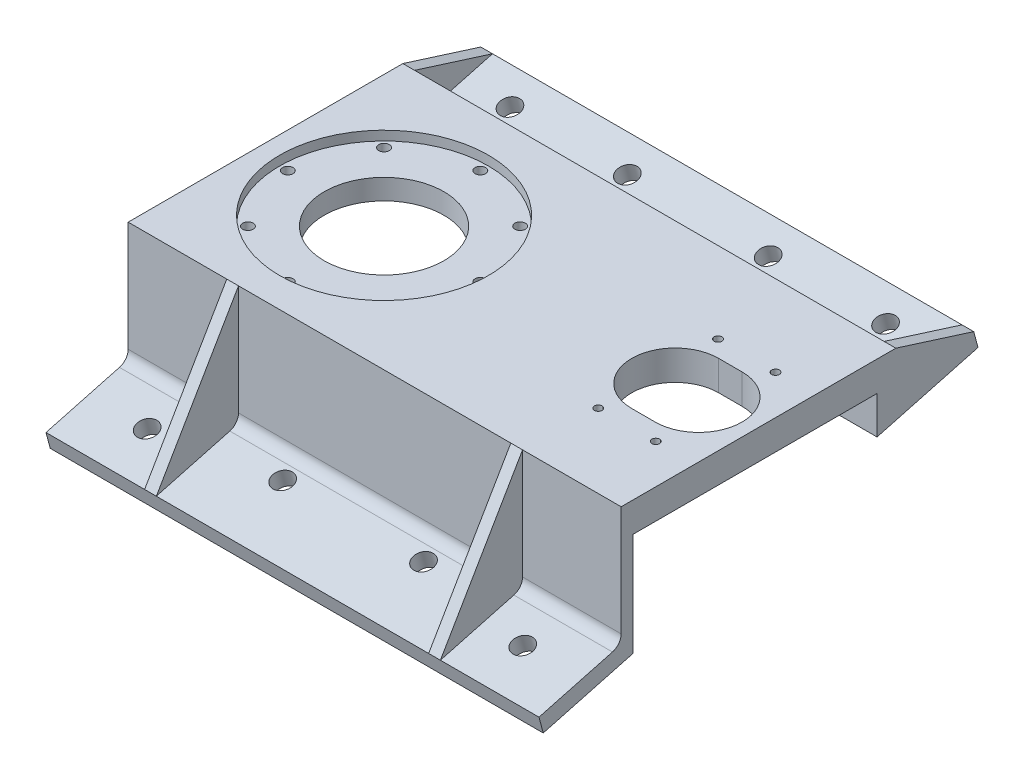
SolidWorks part; units mm, degrees
material "1060 合金"
ref_plane "前视基准面" through (0, 0, 0) normal (0, 0, 1) x (1, 0, 0)
ref_plane "上视基准面" through (0, 0, 0) normal (0, 1, 0) x (1, 0, 0)
ref_plane "右视基准面" through (0, 0, 0) normal (1, 0, 0) x (0, 0, -1)
sketch "草图1" plane through (0, 0, 0) normal (0, 1, 0) x (1, 0, 0)
  line L0 (0, 0) -> (170, 0) construction
  line L1 (170, 31.93) -> (170, -31.93)
  line L2 (15.8391, 73.3084) -> (162.1119, 41.7045)
  line L3 (15.8391, -73.3084) -> (162.1119, -41.7045)
  arc A0 (15.8391, 73.3084) -> (15.8391, -73.3084) centre (0, 0) ccw
  arc A1 (162.1119, -41.7045) -> (170, -31.93) centre (160, -31.93) ccw
  arc A2 (170, 31.93) -> (162.1119, 41.7045) centre (160, 31.93) ccw
  point P6 (170, 0)
  dimension "D1" = 150
  dimension "D4" = 20
  dimension "D5" = 20
  dimension "D2" = 170
  dimension "D3" = 63.86
extrude "凸台-拉伸1" add sketch "草图1" along normal blind 30
sketch "草图2" plane through (0, 30, 0) normal (0, 1, 0) x (1, 0, 0)
  circle A0 centre (0, 0) radius 44.45
  dimension "D1" = 88.9
extrude "切除-拉伸1" cut sketch "草图2" against normal blind 4
sketch "草图3" plane through (0, 26, 0) normal (0, 1, 0) x (1, 0, 0)
  line L0 (0, 0) -> (0, 90.3276) construction
  circle A0 centre (0, 0) radius 25.5
  circle A1 centre (0, 41) radius 2.25
  circle A2 centre (28.9914, 28.9914) radius 2.25
  circle A3 centre (41, 0) radius 2.25
  circle A4 centre (28.9914, -28.9914) radius 2.25
  circle A5 centre (0, -41) radius 2.25
  circle A6 centre (-28.9914, -28.9914) radius 2.25
  circle A7 centre (-41, 0) radius 2.25
  circle A8 centre (-28.9914, 28.9914) radius 2.25
  dimension "D1" = 51
  dimension "D3" = 4.5
  dimension "D2" = 41
  dimension "D4" = 8
extrude "切除-拉伸2" cut sketch "草图3" against normal through all contours A2 | A3 | A4 | A5 | A6 | A7 | A8 | A1 | A0
sketch "草图4" plane through (0, 30, 0) normal (0, 1, 0) x (1, 0, 0)
  line L0 (0, 0) -> (134, 0) construction
  line L1 (124, 18.5) -> (134, 18.5)
  line L2 (124, -18.5) -> (134, -18.5)
  arc A0 (134, -18.5) -> (134, 18.5) centre (134, 0) ccw
  arc A1 (124, 18.5) -> (124, -18.5) centre (124, 0) ccw
  dimension "D2" = 37
  dimension "D3" = 37
  dimension "D1" = 134
  dimension "D4" = 10
extrude "切除-拉伸3" cut sketch "草图4" against normal through all
sketch "草图5" plane through (0, 30, 0) normal (0, 1, 0) x (1, 0, 0)
  arc A0 (134, -18.5) -> (134, 18.5) centre (134, 0) ccw construction
  arc A1 (124, 18.5) -> (124, -18.5) centre (124, 0) ccw construction
  arc A2 (134, -18.5) -> (134, 18.5) centre (134, 0) ccw construction
  arc A3 (124, 18.5) -> (124, -18.5) centre (124, 0) ccw construction
  circle A4 centre (116.75, 25.5) radius 1.65
  circle A5 centre (141.25, 25.5) radius 1.65
  circle A6 centre (141.25, -25.5) radius 1.65
  circle A7 centre (116.75, -25.5) radius 1.65
  dimension "D1" = 3.3
  dimension "D2" = 3.3
  dimension "D3" = 3.3
  dimension "D4" = 3.3
  dimension "D7" = 25.5
  dimension "D5" = 7.25
  dimension "D6" = 25.5
  dimension "D8" = 7.25
  dimension "D9" = 7.25
extrude "切除-拉伸4" cut sketch "草图5" against normal through all
sketch "草图6" plane through (0, 30, 0) normal (0, 1, 0) x (1, 0, 0)
  line L0 (158, 42.5929) -> (158, -42.5929) construction
  line L2 (-52, 54.0463) -> (-52, -54.0463) construction
  line L6 (162.1119, 41.7045) -> (15.8391, 73.3084) construction
  line L7 (15.8391, -73.3084) -> (162.1119, -41.7045) construction
  line L8 (-52, 95) -> (-52, -95)
  line L9 (158, 95) -> (158, -95)
  line L10 (-52, 95) -> (158, 95)
  line L11 (-52, -95) -> (158, -95)
  line L15 (162.1119, 41.7045) -> (15.8391, 73.3084)
  line L16 (15.8391, -73.3084) -> (162.1119, -41.7045)
  line L17 (170, -31.93) -> (170, 31.93)
  line L18 (162.1119, 41.7045) -> (15.8391, 73.3084)
  line L19 (15.8391, -73.3084) -> (162.1119, -41.7045)
  line L20 (170, -31.93) -> (170, 31.93)
  arc A0 (15.8391, 73.3084) -> (15.8391, -73.3084) centre (0, 0) ccw construction
  arc A6 (170, 31.93) -> (162.1119, 41.7045) centre (160, 31.93) ccw
  arc A7 (15.8391, 73.3084) -> (15.8391, -73.3084) centre (0, 0) ccw
  arc A8 (162.1119, -41.7045) -> (170, -31.93) centre (160, -31.93) ccw
  arc A9 (170, 31.93) -> (162.1119, 41.7045) centre (160, 31.93) ccw
  arc A10 (15.8391, 73.3084) -> (15.8391, -73.3084) centre (0, 0) ccw
  arc A11 (162.1119, -41.7045) -> (170, -31.93) centre (160, -31.93) ccw
  point P8 (-52, 0)
  point P13 (158, 0)
  line M26 (162.1119, 41.7045) -> (15.8391, 73.3084)
  arc M27 (15.8391, 73.3084) -> (15.8391, -73.3084) centre (0, 0) ccw
  line M28 (15.8391, -73.3084) -> (162.1119, -41.7045)
  dimension "D3" = 190
  dimension "D1" = 210
  dimension "D2" = 52
  dimension "D4" = 190
  dimension "D5" = 0
extrude "凸台-拉伸2" add sketch "草图6" against normal blind 30 contours L10 L8 L9 M27 M26 | L8 L11 L9 M28 M27
sketch "草图7" plane through (0, 30, 0) normal (0, 1, 0) x (1, 0, 0)
  line L0 (-52, 54.0463) -> (-52, -54.0463)
  line L1 (158, 42.5929) -> (158, -42.5929)
  line L9 (162.1119, 41.7045) -> (158, 42.5929)
  line L10 (158, 42.5929) -> (158, 95)
  line L11 (158, 95) -> (-52, 95)
  line L12 (-52, 95) -> (-52, 54.0463)
  line L13 (-52, -54.0463) -> (-52, -95)
  line L14 (-52, -95) -> (158, -95)
  line L15 (158, -95) -> (158, -42.5929)
  line L16 (158, -42.5929) -> (162.1119, -41.7045)
  line L17 (170, -31.93) -> (170, 31.93)
  line L18 (162.1119, 41.7045) -> (158, 42.5929)
  line L21 (-52, 95) -> (-52, 54.0463)
  line L25 (158, -42.5929) -> (162.1119, -41.7045)
  line L26 (170, -31.93) -> (170, 31.93)
  arc A3 (170, 31.93) -> (162.1119, 41.7045) centre (160, 31.93) ccw
  arc A4 (-52, 54.0463) -> (-52, -54.0463) centre (0, 0) ccw
  arc A5 (162.1119, -41.7045) -> (170, -31.93) centre (160, -31.93) ccw
  arc A6 (170, 31.93) -> (162.1119, 41.7045) centre (160, 31.93) ccw
  arc A7 (-52, 54.0463) -> (-52, -54.0463) centre (0, 0) ccw
  arc A8 (162.1119, -41.7045) -> (170, -31.93) centre (160, -31.93) ccw
  arc M22 (170, 31.93) -> (162.1119, 41.7045) centre (160, 31.93) ccw
  line M23 (162.1119, 41.7045) -> (158, 42.5929)
  arc M27 (-52, 54.0463) -> (-52, -54.0463) centre (0, 0) ccw
  line M31 (158, -42.5929) -> (162.1119, -41.7045)
  arc M32 (162.1119, -41.7045) -> (170, -31.93) centre (160, -31.93) ccw
  line M33 (170, -31.93) -> (170, 31.93)
  dimension "D1" = 0
extrude "切除-拉伸5" cut sketch "草图7" against normal through all contours L0 M27 | L1 M23 M31 M32 M33 M22
sketch "草图9" plane through (-52, 0, 0) normal (-1, 0, 0) x (0, 0, 1)
  line L0 (-95, 20) -> (-60, 10.6218)
  line L1 (-95, 30) -> (95, 30) construction
  line L3 (-60, 10.6218) -> (-60, 30)
  line L5 (-95, 0) -> (-95, 30) construction
  line L7 (-95, 20) -> (-95, 30)
  line L8 (-95, 30) -> (-60, 30)
  dimension "D1" = 15
  dimension "D3" = 19.3782
  dimension "D4" = 35
  dimension "D5" = 10
extrude "切除-拉伸7" cut sketch "草图9" against normal through all contours L8 L3 L0 L7
sketch "草图8" plane through (-52, 0, 0) normal (-1, 0, 0) x (0, 0, 1)
  line L0 (0, 0) -> (52, 0)
  line L1 (-95, 0) -> (95, 0) construction
  line L2 (52, 0) -> (52, 17.3)
  line L3 (52, 17.3) -> (-52, 17.3)
  line L4 (-52, 17.3) -> (-52, 0)
  line L5 (-52, 0) -> (0, 0)
  line L6 (-60, 30) -> (95, 30) construction
  dimension "D1" = 52
  dimension "D2" = 52
  dimension "D3" = 12.7
sketch "草图10" plane through (-52, 0, 0) normal (-1, 0, 0) x (0, 0, 1)
  line L0 (-95, 12.7531) -> (-47.4049, 0) construction
  line L1 (-95, 0) -> (-95, 20) construction
  line L2 (-95, 0) -> (95, 0) construction
  line L3 (-95, 20) -> (-60, 10.6218) construction
  line L6 (-95, 12.7531) -> (-52, 1.2313)
  line L7 (-52, 1.2313) -> (-52, 0)
  line L8 (-95, 12.7531) -> (-95, 0)
  line L9 (-95, 0) -> (-52, 0)
  line L10 (-52, 17.3) -> (-52, 0) construction
  dimension "D1" = 7
extrude "切除-拉伸8" cut sketch "草图10" against normal through all
extrude "切除-拉伸9" cut sketch "草图8" against normal through all
fillet "圆角1" radius 5 1 edges at (53, 10.6218, -60)
sketch "草图11" plane through (-52, 0, 0) normal (-1, 0, 0) x (0, 0, 1)
  line L0 (-95, 12.7531) -> (-93.1883, 19.5145)
  line L1 (-95, 20) -> (-66.2941, 12.3083) construction
  line L2 (-93.1883, 19.5145) -> (-95, 20)
  line L3 (-95, 20) -> (-95, 12.7531)
extrude "切除-拉伸10" cut sketch "草图11" against normal through all
sketch "草图12" plane through (-52, 0, 0) normal (-1, 0, 0) x (0, 0, 1)
  line L0 (-93.1883, 19.5145) -> (-60, 30)
  line L10 (-93.1883, 19.5145) -> (-95, 12.7531)
  line L11 (-95, 12.7531) -> (-52, 1.2313)
  line L12 (-52, 1.2313) -> (-52, 17.3)
  line L13 (-52, 17.3) -> (52, 17.3)
  line L14 (52, 17.3) -> (52, 0)
  line L15 (52, 0) -> (95, 0)
  line L16 (95, 0) -> (95, 30)
  line L17 (95, 30) -> (-60, 30)
  line L18 (-60, 30) -> (-60, 17.1379)
  line L19 (-66.2941, 12.3083) -> (-93.1883, 19.5145)
  line L28 (-60, 30) -> (-60, 17.1379)
  line L29 (-66.2941, 12.3083) -> (-93.1883, 19.5145)
  arc A1 (-66.2941, 12.3083) -> (-60, 17.1379) centre (-65, 17.1379) ccw
  arc A2 (-66.2941, 12.3083) -> (-60, 17.1379) centre (-65, 17.1379) ccw
  dimension "D1" = 0
extrude "凸台-拉伸3" add sketch "草图12" against normal blind 5
sketch "草图13" plane through (158, 0, 0) normal (1, 0, 0) x (0, 0, -1)
  line L3 (66.2941, 12.3083) -> (93.1883, 19.5145)
  line L4 (93.1883, 19.5145) -> (60, 30)
  line L5 (60, 30) -> (60, 17.1379)
  line L6 (66.2941, 12.3083) -> (93.1883, 19.5145)
  line L7 (93.1883, 19.5145) -> (60, 30)
  line L8 (60, 30) -> (60, 17.1379)
  arc A1 (60, 17.1379) -> (66.2941, 12.3083) centre (65, 17.1379) ccw
  arc A2 (60, 17.1379) -> (66.2941, 12.3083) centre (65, 17.1379) ccw
  dimension "D1" = 0
extrude "凸台-拉伸4" add sketch "草图13" against normal blind 5
sketch "草图14" plane through (0, -5.0897, -1.3638) normal (0, 0.9659, 0.2588) x (1, 0, 0)
  line L0 (153, 67.2208) -> (153, 95.0637) construction
  line L3 (153, 95.0637) -> (-47, 95.0637) construction
  circle A0 centre (-27, 82.0637) radius 4.25
  circle A1 centre (23, 82.0637) radius 4.25
  circle A2 centre (83, 82.0637) radius 4.25
  circle A3 centre (133, 82.0637) radius 4.25
  dimension "D1" = 8.5
  dimension "D2" = 160
  dimension "D3" = 20
  dimension "D4" = 50
  dimension "D5" = 50
  dimension "D6" = 13
extrude "切除-拉伸11" cut sketch "草图14" against normal through all
sketch "草图16" plane through (-52, 0, 0) normal (-1, 0, 0) x (0, 0, 1)
  line L0 (-60, 30) -> (95, 30) construction
  line L1 (95, 0) -> (52, 0)
  line L2 (95, 0) -> (95, 30)
  line L3 (95, 30) -> (52, 30)
  line L4 (52, 0) -> (52, 30)
extrude "切除-拉伸12" cut sketch "草图16" against normal through all
ref_plane "基准面1" through (0, -11.8512, -3.1755) normal (0, -0.9659, -0.2588) x (-1, 0, 0)
sketch "草图18" plane through (0, 30, 0) normal (0, 1, 0) x (1, 0, 0)
  line L1 (-52, -52) -> (158, -52)
  line L2 (-52, -52) -> (-52, -57)
  line L3 (-52, -57) -> (158, -57)
  line L4 (158, -52) -> (158, -57)
  dimension "D1" = 5
extrude "凸台-拉伸7" add sketch "草图18" against normal up to surface (56.6355 mm away) up to plane "基准面1"
sketch "草图19" plane through (-52, 0, 0) normal (-1, 0, 0) x (0, 0, 1)
  line L0 (57, -27.9752) -> (90.1883, -36.868)
  line L1 (90.1883, -36.868) -> (92, -30.1065)
  line L2 (92, -30.1065) -> (57, -20.7283)
  line L3 (57, -27.9752) -> (57, 30) construction
  line L4 (57, -20.7283) -> (57, -27.9752)
  line L5 (52, -26.6355) -> (57, -27.9752) construction
  dimension "D1" = 7
  dimension "D2" = 40
extrude "凸台-拉伸8" add sketch "草图19" against normal up to surface (210 mm away) up to face at (158, 8.1654, -14.9098)
sketch "草图20" plane through (-52, 0, 0) normal (-1, 0, 0) x (0, 0, 1)
  line L0 (92, -30.1065) -> (57, -20.7283) construction
  line L1 (57, -20.7283) -> (57, 30) construction
  line L2 (92, -30.1065) -> (57, -20.7283)
  line L3 (57, -20.7283) -> (57, 30)
  line L4 (57, 30) -> (92, -30.1065)
extrude "凸台-拉伸9" add sketch "草图20" against normal blind 5
sketch "草图21" plane through (158, 0, 0) normal (1, 0, 0) x (0, 0, -1)
  line L3 (-57, 30) -> (-92, -30.1065)
  line L4 (-92, -30.1065) -> (-57, -20.7283)
  line L5 (-57, -20.7283) -> (-57, 30)
  line L6 (-57, 30) -> (-92, -30.1065)
  line L7 (-92, -30.1065) -> (-57, -20.7283)
  line L8 (-57, -20.7283) -> (-57, 30)
  dimension "D1" = 0
extrude "凸台-拉伸10" add sketch "草图21" against normal blind 5
sketch "草图22" plane through (0, -5.0897, -1.3638) normal (0, 0.9659, 0.2588) x (1, 0, 0)
  line L0 (-47, -96.6573) -> (-47, -47.2932) construction
  line L2 (153, -96.6573) -> (153, -60.4226) construction
  circle A0 centre (-27, -77.9363) radius 4.25
  circle A1 centre (23, -69.9363) radius 4.25
  circle A2 centre (83, -69.9363) radius 4.25
  circle A3 centre (133, -77.9363) radius 4.25
  circle A4 centre (133, 82.0637) radius 4.25 construction
  circle A5 centre (-27, 82.0637) radius 4.25 construction
  circle A6 centre (23, 82.0637) radius 4.25 construction
  circle A7 centre (83, 82.0637) radius 4.25 construction
  dimension "D1" = 8.5
  dimension "D7" = 152
  dimension "D6" = 152
  dimension "D8" = 50
  dimension "D4" = 160
  dimension "D5" = 160
  dimension "D2" = 20
  dimension "D3" = 20
  dimension "D9" = 50
extrude "切除-拉伸13" cut sketch "草图22" against normal through all
fillet "圆角2" radius 5 1 edges at (53, -20.7283, 57)
ref_plane "基准面2" through (-7.5, 0, 0) normal (-1, 0, 0) x (0, 0, 1)
ref_plane "基准面3" through (113.5, 0, 0) normal (1, 0, 0) x (0, 0, -1)
sketch "草图25" plane through (-7.5, 0, 0) normal (-1, 0, 0) x (0, 0, 1)
  line L3 (60.7059, -21.7213) -> (92, -30.1065)
  line L4 (57, 30) -> (57, -16.8916)
  line L5 (92, -30.1065) -> (57, 30)
  line L6 (60.7059, -21.7213) -> (92, -30.1065)
  line L7 (57, 30) -> (57, -16.8916)
  line L8 (92, -30.1065) -> (57, 30)
  arc A1 (57, -16.8916) -> (60.7059, -21.7213) centre (62, -16.8916) ccw
  arc A2 (57, -16.8916) -> (60.7059, -21.7213) centre (62, -16.8916) ccw
  dimension "D1" = 0
extrude "凸台-拉伸11" add sketch "草图25" along normal mid plane 5
sketch "草图26" plane through (113.5, 0, 0) normal (1, 0, 0) x (0, 0, -1)
  line L3 (-57, -16.8916) -> (-57, 30)
  line L4 (-92, -30.1065) -> (-60.7059, -21.7213)
  line L5 (-57, 30) -> (-92, -30.1065)
  line L6 (-57, -16.8916) -> (-57, 30)
  line L7 (-92, -30.1065) -> (-60.7059, -21.7213)
  line L8 (-57, 30) -> (-92, -30.1065)
  arc A1 (-60.7059, -21.7213) -> (-57, -16.8916) centre (-62, -16.8916) ccw
  arc A2 (-60.7059, -21.7213) -> (-57, -16.8916) centre (-62, -16.8916) ccw
  dimension "D1" = 0
extrude "凸台-拉伸12" add sketch "草图26" along normal mid plane 5
sketch "草图27" plane through (-47, 0, 0) normal (1, 0, 0) x (0, 0, -1)
  line L3 (-92, -30.1065) -> (-60.7059, -21.7213)
  line L4 (-57, -16.8916) -> (-57, 30)
  line L5 (-57, 30) -> (-92, -30.1065)
  line L6 (-92, -30.1065) -> (-60.7059, -21.7213)
  line L7 (-57, -16.8916) -> (-57, 30)
  line L8 (-57, 30) -> (-92, -30.1065)
  arc A1 (-60.7059, -21.7213) -> (-57, -16.8916) centre (-62, -16.8916) ccw
  arc A2 (-60.7059, -21.7213) -> (-57, -16.8916) centre (-62, -16.8916) ccw
  dimension "D1" = 0
extrude "切除-拉伸15" cut sketch "草图27" against normal blind 5
sketch "草图28" plane through (153, 0, 0) normal (-1, 0, 0) x (0, 0, 1)
  line L3 (57, 30) -> (57, -16.8916)
  line L4 (60.7059, -21.7213) -> (92, -30.1065)
  line L5 (92, -30.1065) -> (57, 30)
  line L6 (57, 30) -> (57, -16.8916)
  line L7 (60.7059, -21.7213) -> (92, -30.1065)
  line L8 (92, -30.1065) -> (57, 30)
  arc A1 (57, -16.8916) -> (60.7059, -21.7213) centre (62, -16.8916) ccw
  arc A2 (57, -16.8916) -> (60.7059, -21.7213) centre (62, -16.8916) ccw
  dimension "D1" = 0
extrude "切除-拉伸16" cut sketch "草图28" against normal blind 5
